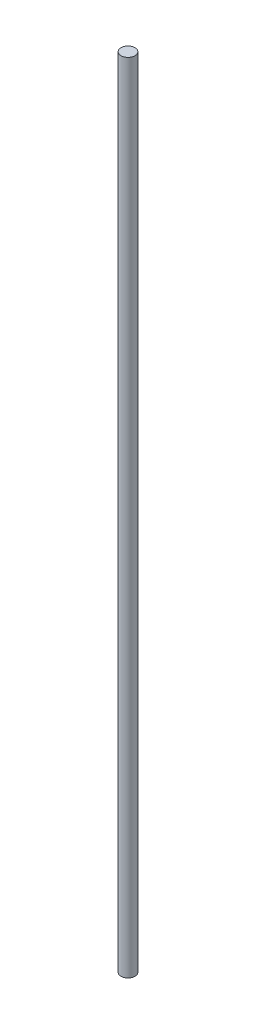
SolidWorks part; units mm, degrees
material "201 Annealed Stainless Steel (SS)"
ref_plane "Front Plane" through (0, 0, 0) normal (0, 0, 1) x (1, 0, 0)
ref_plane "Top Plane" through (0, 0, 0) normal (0, 1, 0) x (1, 0, 0)
ref_plane "Right Plane" through (0, 0, 0) normal (1, 0, 0) x (0, 0, -1)
sketch "Sketch1" plane through (0, 0, 0) normal (0, 1, 0) x (1, 0, 0)
  circle A0 centre (0, 0) radius 4
  dimension "D1" = 8
extrude "Boss-Extrude1" add sketch "Sketch1" along normal blind 457
